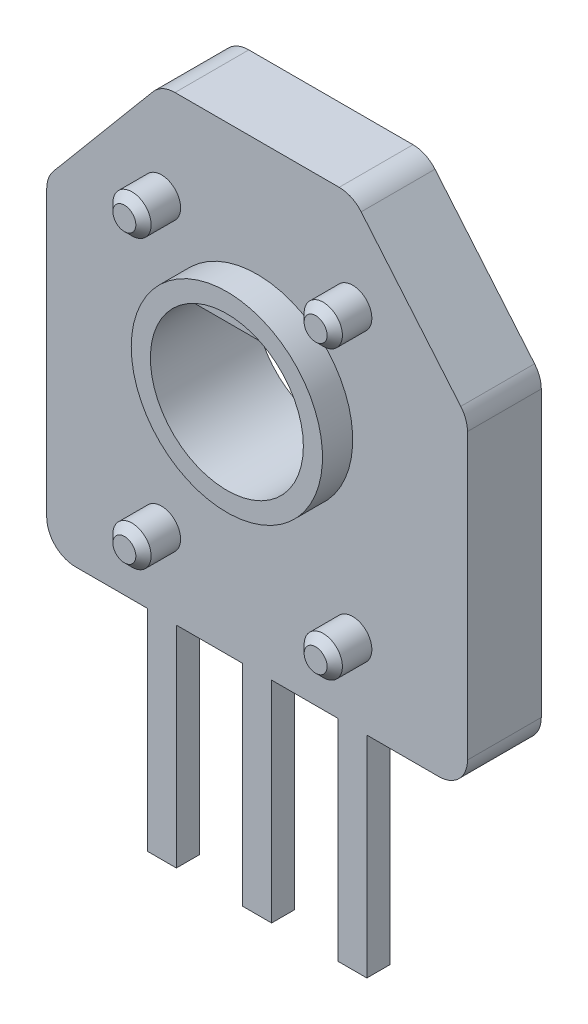
SolidWorks part; units mm, degrees
ref_plane "Front Plane" through (0, 0, 0) normal (0, 0, 1) x (1, 0, 0)
ref_plane "Top Plane" through (0, 0, 0) normal (0, 1, 0) x (1, 0, 0)
ref_plane "Right Plane" through (0, 0, 0) normal (1, 0, 0) x (0, 0, -1)
sketch "Sketch1" plane through (0, 0, 0) normal (0, 0, 1) x (1, 0, 0)
  line L0 (5.5, 0) -> (5.5, -6.5)
  line L1 (5.5, -6.5) -> (-5.5, -6.5)
  line L2 (-5.5, -6.5) -> (-5.5, 0)
  line L3 (-5.5, 0) -> (5.5, 0) construction
  line L4 (-5.5, 0) -> (-5.5, 1.96)
  line L5 (-5.5, 1.96) -> (-2.496, 5.54)
  line L6 (-2.496, 5.54) -> (2.496, 5.54)
  line L7 (2.496, 5.54) -> (5.5, 1.96)
  line L8 (5.5, 1.96) -> (5.5, 0)
  line L9 (-5.5, 1.96) -> (-5.5, 12.411) construction
  line L10 (-1.7186, 1.023) -> (1.7186, 1.023)
  arc A0 (-1.7186, 1.023) -> (1.7186, 1.023) centre (0, 0) ccw
  point P6 (0, -6.5)
  point P12 (0, 0)
  point P16 (0, -2)
  dimension "D1" = 4
  dimension "D2" = 11
  dimension "D3" = 6.5
  dimension "D4" = 5.54
  dimension "D5" = 3.58
  dimension "D6" = 40
  dimension "D7" = 3.023
extrude "Boss-Extrude1" add sketch "Sketch1" along normal blind 1.93
sketch "Sketch2" plane through (0, 0, 1.93) normal (0, 0, 1) x (1, 0, 0)
  circle A0 centre (0, 0) radius 2 construction
  circle A1 centre (0, 0) radius 2
  circle A2 centre (0, 0) radius 2.5
  dimension "D1" = 0.5
extrude "Boss-Extrude2" add sketch "Sketch2" along normal blind 0.79
sketch "Sketch3" plane through (0, 0, 1.93) normal (0, 0, 1) x (1, 0, 0)
  line L0 (0, -6.5) -> (2.49, -6.5) construction
  line L1 (-2.49, -6.5) -> (0, -6.5) construction
  line L5 (-5.5, -6.5) -> (5.5, -6.5) construction
  line L6 (-0.38, -6.5) -> (0.38, -6.5)
  line L7 (-0.38, -6.5) -> (-0.38, -7.1)
  line L8 (-0.38, -7.1) -> (0.38, -7.1)
  line L9 (0.38, -6.5) -> (0.38, -7.1)
  line L10 (2.11, -6.5) -> (2.11, -7.1)
  line L11 (2.11, -6.5) -> (2.87, -6.5)
  line L12 (2.87, -6.5) -> (2.87, -7.1)
  line L13 (2.11, -7.1) -> (2.87, -7.1)
  line L14 (-2.87, -6.5) -> (-2.87, -7.1)
  line L15 (-2.87, -6.5) -> (-2.11, -6.5)
  line L16 (-2.11, -6.5) -> (-2.11, -7.1)
  line L17 (-2.87, -7.1) -> (-2.11, -7.1)
  point P12 (0, -6.5)
  dimension "D1" = 0.6
  dimension "D2" = 0.76
  dimension "D5" = 2.49
  dimension "D6" = 2.49
  dimension "D3" = 2
  dimension "D4" = 2
fillet "Fillet2" radius 0.75 6 edges at (5.5, -6.5, 0.965) (5.5, 1.96, 0.965) (2.496, 5.54, 0.965) (-2.496, 5.54, 0.965) (-5.5, -6.5, 0.965) (-5.5, 1.96, 0.965)
sketch "Sketch5" plane through (0, 0, 1.93) normal (0, 0, 1) x (1, 0, 0)
  line L1 (-2.5, -4.5) -> (2.5, -4.5) construction
  line L2 (-2.5, -4.5) -> (-2.5, 3) construction
  line L3 (-2.5, 3) -> (2.5, 3) construction
  line L4 (2.5, -4.5) -> (2.5, 3) construction
  line L5 (-2.5, -4.5) -> (2.5, 3) construction
  line L6 (-2.5, 3) -> (2.5, -4.5) construction
  circle A0 centre (-2.5, -4.5) radius 0.5
  circle A1 centre (2.5, -4.5) radius 0.5
  circle A2 centre (2.5, 3) radius 0.5
  circle A3 centre (-2.5, 3) radius 0.5
  point P0 (0, -0.75)
  dimension "D4" = 1
  dimension "D1" = 5
  dimension "D2" = 7.5
  dimension "D3" = 3
extrude "Boss-Extrude4" add sketch "Sketch5" along normal blind 0.97
chamfer "Chamfer1" distance 0.2 angle 45 4 edges at (-2, -4.5, 2.9) (3, -4.5, 2.9) (3, 3, 2.9) (-2, 3, 2.9)
sketch "Sketch6" plane through (0, -6.5, 0) normal (0, -1, 0) x (1, 0, 0)
  line L0 (-2.87, 1.93) -> (-2.11, 1.93) construction
  line L1 (-2.87, 1.93) -> (-2.11, 1.93)
  line L2 (-2.87, 1.93) -> (-2.87, 1.33)
  line L3 (-2.87, 1.33) -> (-2.11, 1.33)
  line L4 (-2.11, 1.93) -> (-2.11, 1.33)
  line L5 (-0.38, 1.93) -> (0.38, 1.93) construction
  line L6 (-0.38, 1.93) -> (0.38, 1.93)
  line L7 (-0.38, 1.93) -> (-0.38, 1.33)
  line L8 (-0.38, 1.33) -> (0.38, 1.33)
  line L9 (0.38, 1.93) -> (0.38, 1.33)
  line L10 (2.11, 1.93) -> (2.87, 1.93) construction
  line L11 (2.11, 1.93) -> (2.87, 1.93)
  line L12 (2.11, 1.93) -> (2.11, 1.33)
  line L13 (2.11, 1.33) -> (2.87, 1.33)
  line L14 (2.87, 1.93) -> (2.87, 1.33)
  line L15 (2.11, 1.93) -> (2.87, 1.93) construction
  line L16 (0, 1.93) -> (2.49, 1.93) construction
  line L17 (-2.87, 1.93) -> (-2.11, 1.93) construction
  line L18 (-2.49, 1.93) -> (0, 1.93) construction
  point P18 (2.87, 1.93)
  point P21 (0.38, 1.93)
  point P24 (-2.11, 1.93)
  dimension "D1" = 0.6
extrude "Boss-Extrude5" add sketch "Sketch6" along normal blind 5.5
